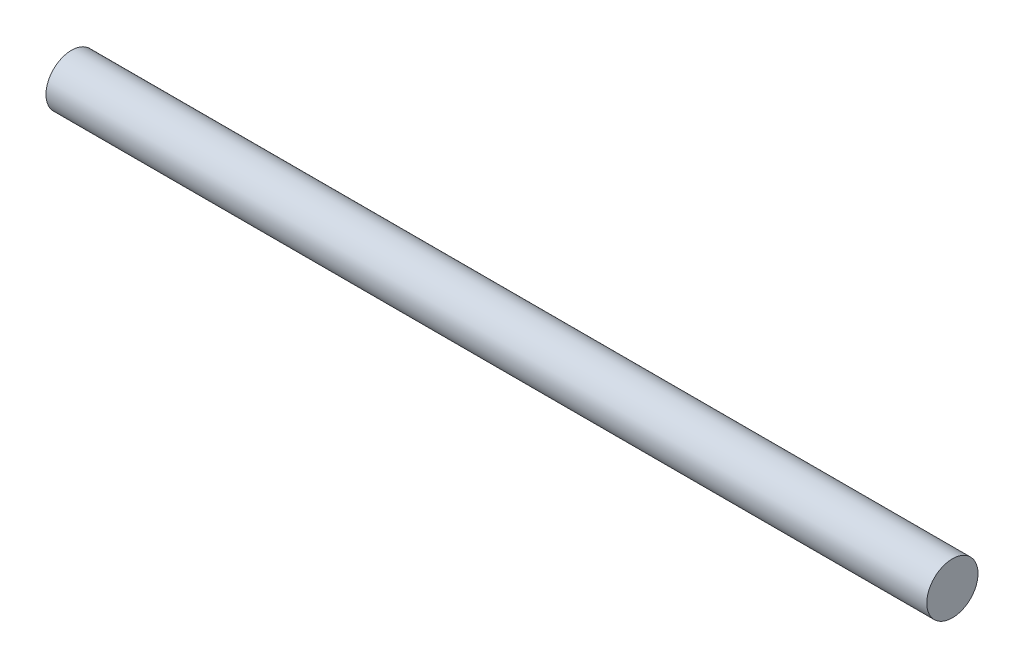
SolidWorks part; units mm, degrees
ref_plane "Front Plane" through (0, 0, 0) normal (0, 0, 1) x (1, 0, 0)
ref_plane "Top Plane" through (0, 0, 0) normal (0, 1, 0) x (1, 0, 0)
ref_plane "Right Plane" through (0, 0, 0) normal (1, 0, 0) x (0, 0, -1)
sketch "Sketch1" plane through (0, 0, 0) normal (1, 0, 0) x (0, 0, -1)
  circle A0 centre (0, 0) radius 2.5
  dimension "D1" = 5
extrude "Boss-Extrude1" add sketch "Sketch1" along normal blind 86
